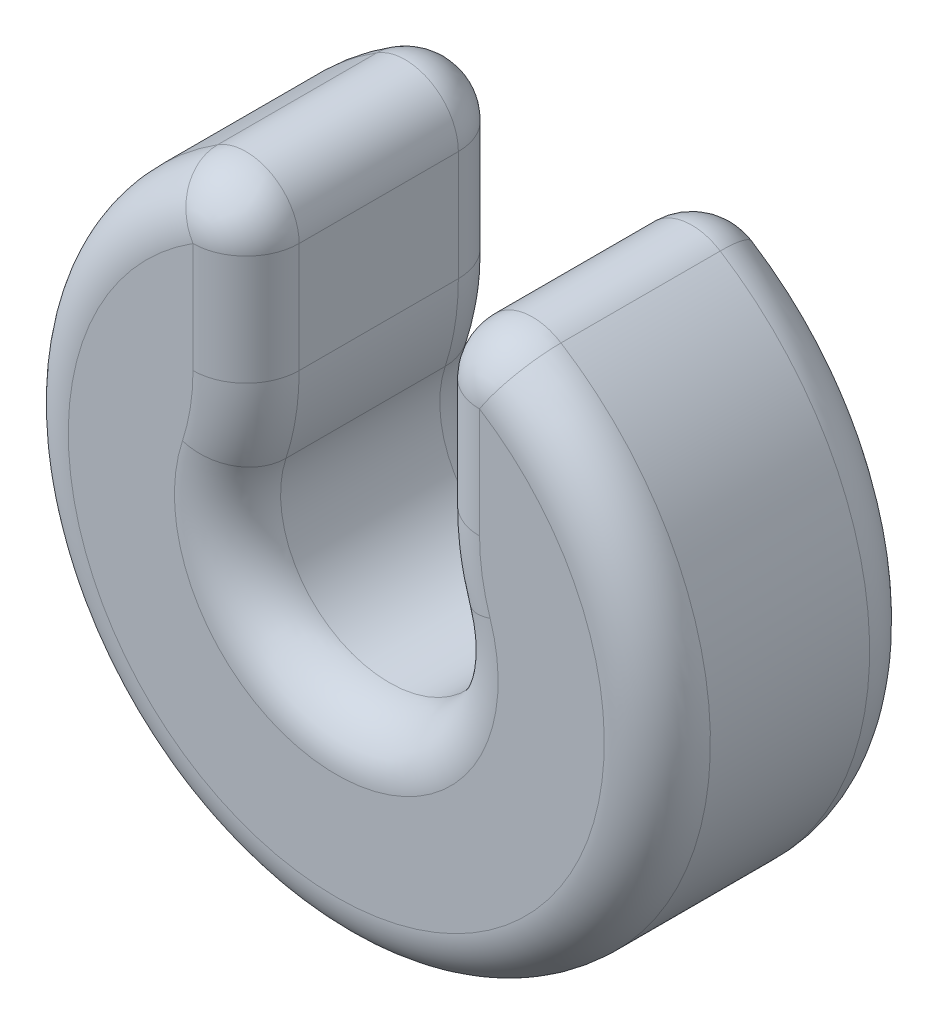
SolidWorks part; units mm, degrees
ref_plane "Front Plane" through (0, 0, 0) normal (0, 0, 1) x (1, 0, 0)
ref_plane "Top Plane" through (0, 0, 0) normal (0, 1, 0) x (1, 0, 0)
ref_plane "Right Plane" through (0, 0, 0) normal (1, 0, 0) x (0, 0, -1)
sketch "Sketch1" plane through (0, 0, 0) normal (0, 0, 1) x (1, 0, 0)
  line L0 (-1.7, 5.8062) -> (-1.7, 1.1456)
  line L1 (0, -2.75) -> (0, 2.75) construction
  line L2 (1.7, 5.8062) -> (1.7, 1.1456)
  arc A0 (-1.7, 1.1456) -> (1.7, 1.1456) centre (0, 0) ccw
  arc A1 (-1.7, 5.8062) -> (1.7, 5.8062) centre (0, 0) ccw
  dimension "D1" = 12.1
  dimension "D2" = 4.1
  dimension "D3" = 1.7
extrude "Boss-Extrude1" add sketch "Sketch1" along normal blind 5
fillet "Fillet1" radius 5 2 edges at (1.7, 1.1456, 2.5) (-1.7, 1.1456, 2.5)
fillet "Fillet3" radius 1 2 edges at (1.7, 5.8062, 2.5) (-1.7, 5.8062, 2.5)
fillet "Fillet4" radius 1 16 edges at (-2.2176, 5.1436, 0) (-1.7, 3.2307, 0) (-1.7624, 1.406, 0) (0, -2.05, 0) (1.7624, 1.406, 0) (1.7, 3.2307, 0) (2.2176, 5.1436, 0) (-2.2176, 5.1436, 5) (-1.7, 3.2307, 5) (-1.7624, 1.406, 5) (0, -2.05, 5) (1.7624, 1.406, 5) (1.7, 3.2307, 5) (2.2176, 5.1436, 5) (0, -6.05, 0) (0, -6.05, 5)
